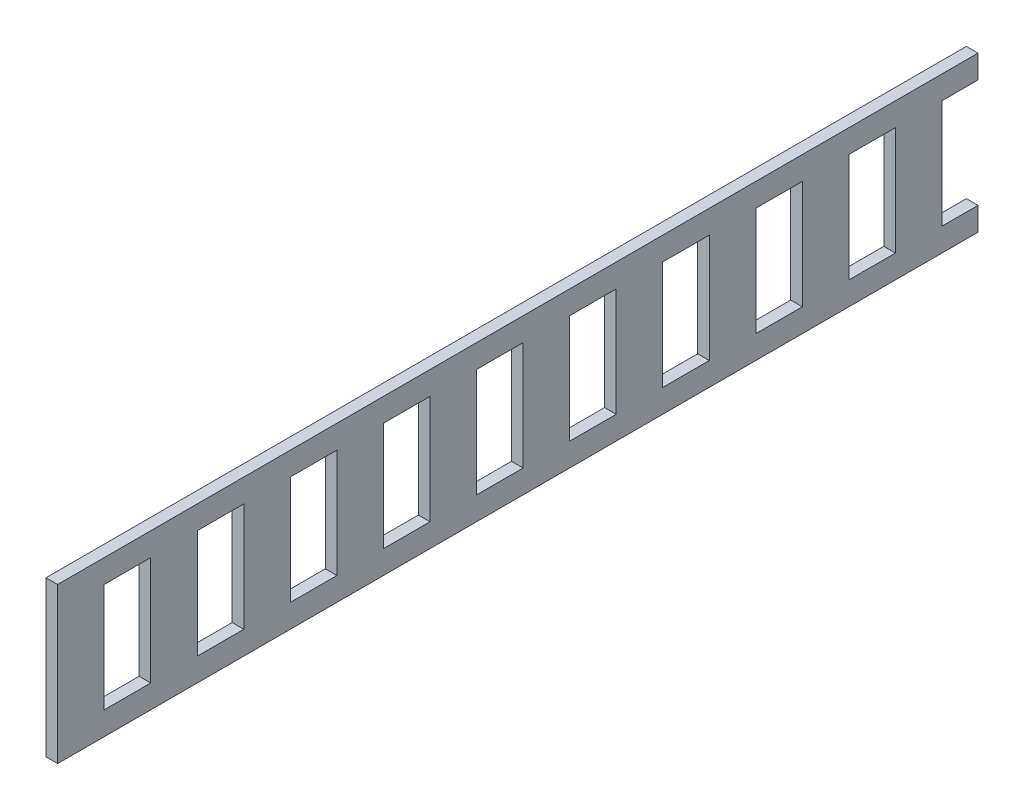
SolidWorks part; units mm, degrees
ref_plane "Front Plane" through (0, 0, 0) normal (0, 0, 1) x (1, 0, 0)
ref_plane "Top Plane" through (0, 0, 0) normal (0, 1, 0) x (1, 0, 0)
ref_plane "Right Plane" through (0, 0, 0) normal (1, 0, 0) x (0, 0, -1)
sketch "Sketch1" plane through (0, 0, 0) normal (1, 0, 0) x (0, 0, -1)
  line L1 (-593.2, 0) -> (593.2, 0)
  line L2 (-593.2, 0) -> (-593.2, 200)
  line L3 (-593.2, 200) -> (593.2, 200)
  line L4 (593.2, 0) -> (593.2, 30)
  line L5 (-533.2, 170) -> (-473.2, 170)
  line L6 (-533.2, 170) -> (-533.2, 30)
  line L7 (-533.2, 30) -> (-473.2, 30)
  line L8 (-473.2, 170) -> (-473.2, 30)
  line L52 (-533.2, 170) -> (-473.2, 170) construction
  line L53 (-413.2, 170) -> (-413.2, 30)
  line L54 (-413.2, 170) -> (-353.2, 170)
  line L55 (-353.2, 170) -> (-353.2, 30)
  line L56 (-413.2, 30) -> (-353.2, 30)
  line L57 (-293.2, 170) -> (-293.2, 30)
  line L58 (-293.2, 170) -> (-233.2, 170)
  line L59 (-233.2, 170) -> (-233.2, 30)
  line L60 (-293.2, 30) -> (-233.2, 30)
  line L61 (-173.2, 170) -> (-173.2, 30)
  line L62 (-173.2, 170) -> (-113.2, 170)
  line L63 (-113.2, 170) -> (-113.2, 30)
  line L64 (-173.2, 30) -> (-113.2, 30)
  line L65 (-53.2, 170) -> (-53.2, 30)
  line L66 (-53.2, 170) -> (6.8, 170)
  line L67 (6.8, 170) -> (6.8, 30)
  line L68 (-53.2, 30) -> (6.8, 30)
  line L69 (66.8, 170) -> (66.8, 30)
  line L70 (66.8, 170) -> (126.8, 170)
  line L71 (126.8, 170) -> (126.8, 30)
  line L72 (66.8, 30) -> (126.8, 30)
  line L73 (186.8, 170) -> (186.8, 30)
  line L74 (186.8, 170) -> (246.8, 170)
  line L75 (246.8, 170) -> (246.8, 30)
  line L76 (186.8, 30) -> (246.8, 30)
  line L77 (306.8, 170) -> (306.8, 30)
  line L78 (306.8, 170) -> (366.8, 170)
  line L79 (366.8, 170) -> (366.8, 30)
  line L80 (306.8, 30) -> (366.8, 30)
  line L81 (426.8, 170) -> (426.8, 30)
  line L82 (426.8, 170) -> (486.8, 170)
  line L83 (486.8, 170) -> (486.8, 30)
  line L84 (426.8, 30) -> (486.8, 30)
  line L85 (546.8, 170) -> (546.8, 30)
  line L86 (546.8, 170) -> (593.2, 170)
  line L88 (546.8, 30) -> (593.2, 30)
  line L89 (-533.2, 170) -> (-413.2, 170) construction
  line L90 (606.8, 170) -> (606.8, 30) [skipped]
  line L91 (593.2, 170) -> (593.2, 200)
  point P4 (0, 0)
  point P10 (-503.2, 170)
  dimension "D1" = 1186.4
  dimension "D2" = 200
  dimension "D3" = 30
  dimension "D4" = 30
  dimension "D5" = 60
  dimension "D6" = 60
  dimension "D8" = 120
  dimension "D7" = 10
extrude "Boss-Extrude1" add sketch "Sketch1" along normal blind 15
